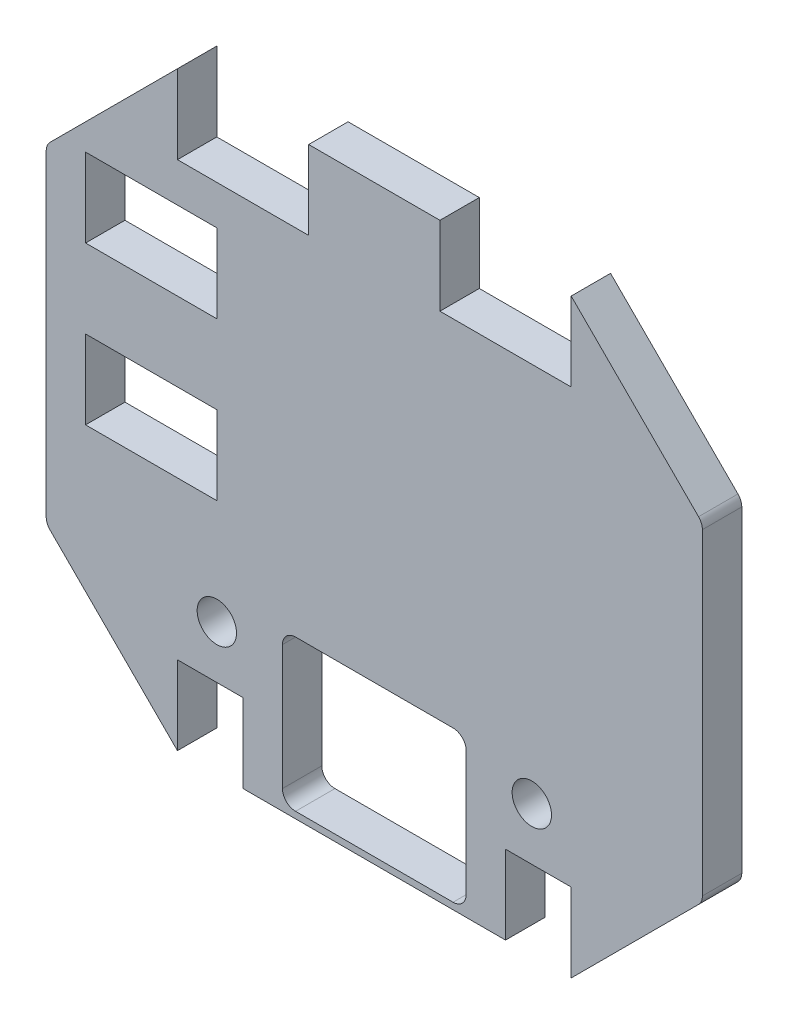
SolidWorks part; units mm, degrees
ref_plane "Front Plane" through (0, 0, 0) normal (0, 0, 1) x (1, 0, 0)
ref_plane "Top Plane" through (0, 0, 0) normal (0, 1, 0) x (1, 0, 0)
ref_plane "Right Plane" through (0, 0, 0) normal (1, 0, 0) x (0, 0, -1)
sketch "Sketch1" plane through (0, 0, 0) normal (0, 0, 1) x (1, 0, 0)
  line L0 (0, 0) -> (0, 25)
  line L1 (0, 25) -> (10, 35)
  line L2 (10, 35) -> (40, 35)
  line L3 (40, 35) -> (50, 25)
  line L4 (50, 25) -> (50, 0)
  line L5 (50, 0) -> (40, -10)
  line L6 (40, -10) -> (10, -10)
  line L7 (10, -10) -> (0, 0)
  line L9 (18, 2) -> (32, 2)
  line L10 (18, 2) -> (18, -9.5)
  line L11 (18, -9.5) -> (32, -9.5)
  line L12 (32, 2) -> (32, -9.5)
  circle A0 centre (13, 0) radius 1.5
  circle A1 centre (37, 0) radius 1.5
  dimension "D3" = 3
  dimension "D2" = 10
  dimension "D1" = 45
  dimension "D4" = 24
  dimension "D5" = 14
  dimension "D6" = 11.5
  dimension "D7" = 5
  dimension "D8" = 2
  dimension "D15" = 50
  dimension "D16" = 30
  dimension "D17" = 18
extrude "Boss-Extrude1" add sketch "Sketch1" along normal blind 3
sketch "Sketch2" plane through (0, 0, 3) normal (0, 0, 1) x (1, 0, 0)
  line L0 (10, -10) -> (40, -10) construction
  line L1 (10, 35) -> (20, 35)
  line L2 (10, 35) -> (10, 29)
  line L3 (10, 29) -> (20, 29)
  line L4 (20, 35) -> (20, 29)
  line L5 (30, 35) -> (40, 35)
  line L6 (30, 35) -> (30, 29)
  line L7 (30, 29) -> (40, 29)
  line L8 (40, 35) -> (40, 29)
  line L9 (10, -4) -> (15, -4)
  line L10 (10, -4) -> (10, -10)
  line L11 (10, -10) -> (15, -10)
  line L12 (15, -4) -> (15, -10)
  line L13 (35, -4) -> (40, -4)
  line L14 (35, -4) -> (35, -10)
  line L15 (35, -10) -> (40, -10)
  line L16 (40, -4) -> (40, -10)
  line L17 (40, 35) -> (10, 35) construction
  dimension "D1" = 6
  dimension "D2" = 10
  dimension "D3" = 5
  dimension "D4" = 30
extrude "Cut-Extrude1" cut sketch "Sketch2" against normal through all
sketch "Sketch3" plane through (0, 0, 3) normal (0, 0, 1) x (1, 0, 0)
  line L1 (3, 14) -> (13, 14)
  line L2 (3, 14) -> (3, 8)
  line L3 (3, 8) -> (13, 8)
  line L4 (13, 14) -> (13, 8)
  line L5 (32, 2) -> (18, 2) construction
  line L6 (0, 25) -> (0, 0) construction
  line L7 (3, 26) -> (13, 26)
  line L8 (3, 26) -> (3, 20)
  line L9 (3, 20) -> (13, 20)
  line L10 (13, 26) -> (13, 20)
  dimension "D1" = 3
  dimension "D2" = 10
  dimension "D3" = 6
  dimension "D4" = 6
  dimension "D5" = 6
extrude "Cut-Extrude2" cut sketch "Sketch3" against normal through all
fillet "Fillet1" radius 1 8 edges at (18, 2, 1.5) (32, 2, 1.5) (32, -9.5, 1.5) (18, -9.5, 1.5) (50, 0, 1.5) (50, 25, 1.5) (0, 0, 1.5) (0, 25, 1.5)
